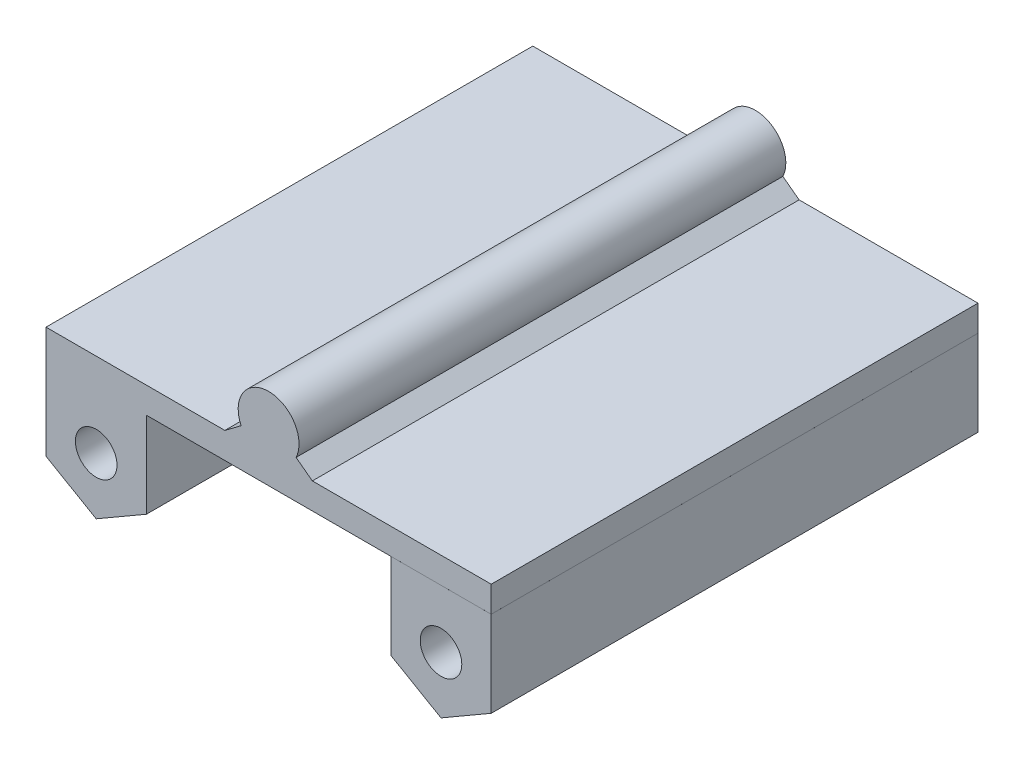
SolidWorks part; units mm, degrees
ref_plane "Front Plane" through (0, 0, 0) normal (0, 0, 1) x (1, 0, 0)
ref_plane "Top Plane" through (0, 0, 0) normal (0, 1, 0) x (1, 0, 0)
ref_plane "Right Plane" through (0, 0, 0) normal (1, 0, 0) x (0, 0, -1)
sketch "Sketch3" plane through (0, 0, 0) normal (0, 0, 1) x (1, 0, 0)
  line L0 (0, 0) -> (4.95, 0)
  line L1 (4.95, 0) -> (4.95, -4.23)
  line L2 (0, 0) -> (0, -4.23)
  line L3 (0, -4.23) -> (2.475, -5.6632)
  line L4 (2.475, -5.6632) -> (4.95, -4.23)
  line L5 (0, 0) -> (10.9749, 0)
  line L6 (14.6231, 0.3758) -> (13.8212, 0.9775)
  line L7 (0, 5) -> (10.975, 5)
  line L18 (17, 0) -> (21.95, 0)
  line L19 (21.95, 0) -> (21.95, -4.23)
  line L20 (17, 0) -> (17, -4.23)
  line L21 (17, -4.23) -> (19.475, -5.6632)
  line L22 (19.475, -5.6632) -> (21.95, -4.23)
  line L23 (13.1316, 1.2844) -> (12.3297, 1.8861)
  line L24 (21.95, 0) -> (21.95, 5)
  line L25 (21.95, 5) -> (10.975, 5)
  line L26 (0, 5) -> (13.7023, 5)
  line L27 (21.9498, -0.0005) -> (10.9749, 0)
  line L28 (0, 0) -> (0, 1.2845)
  line L29 (0, 1.2845) -> (8.8183, 1.2845)
  line L30 (0, 1.2845) -> (0, 0)
  line L31 (21.9498, -0.0005) -> (16.9998, -0.0003)
  line L32 (8.8183, 1.2845) -> (9.6203, 1.8861)
  line L33 (21.9499, 1.284) -> (13.1316, 1.2844)
  line L34 (21.9498, -0.0005) -> (21.9499, 1.284)
  line L35 (10.3099, 0.3759) -> (11.1118, 0.9776)
  arc A1 (12.3297, 1.8861) -> (9.6203, 1.8861) centre (10.975, 2.5301) ccw
  arc A2 (13.8212, 0.9775) -> (11.1118, 0.9776) centre (12.4665, 1.6216) ccw
  dimension "D4" = 3
  dimension "D1" = 4.23
  dimension "D2" = 2.86
  dimension "D3" = 4.23
  dimension "D6" = 5
  dimension "D7" = 2.86
  dimension "D8" = 12.05
  dimension "D9" = 10.975
extrude "Boss-Extrude2" add sketch "Sketch3" along normal blind 24 contours L23 A1 L32 L29 L28 L0 L5 L27 L20 L18 L34 L33 | L3 L4 L1 L0 L2 | L34 L27 L20 L21 L22 L19 L18
sketch "Sketch4" plane through (0, 0, 24) normal (0, 0, 1) x (1, 0, 0)
  line L0 (8.8183, 1.2845) -> (9.6203, 1.8861)
  line L1 (8.8183, 1.2845) -> (9.6203, 1.8861) construction
sketch "Sketch6" plane through (0, 0, 24) normal (0, 0, 1) x (1, 0, 0)
  circle A0 centre (2.475, -2.8632) radius 1.025
  circle A1 centre (19.475, -2.8632) radius 1.025
  dimension "D1" = 2.05
  dimension "D2" = 2.8
  dimension "D3" = 2.05
  dimension "D4" = 2.8
extrude "Cut-Extrude1" cut sketch "Sketch6" against normal blind 5 contours A0 | A1
sketch "Sketch7" plane through (0, 0, 0) normal (0, 0, -1) x (-1, 0, 0)
  line L0 (-2.475, -5.6632) -> (-2.475, -2.8632)
  circle A0 centre (-19.475, -2.8632) radius 1.025
  circle A1 centre (-2.475, -2.8632) radius 1.025
  dimension "D1" = 2.05
  dimension "D2" = 2.8
  dimension "D3" = 2.05
  dimension "D4" = 2.8
extrude "Cut-Extrude2" cut sketch "Sketch7" against normal blind 5
sketch "Sketch8" plane through (0, 0, 5) normal (0, 0, -1) x (-1, 0, 0)
  line L0 (-19.475, -2.8632) -> (-18.45, -2.8632)
  line L1 (-2.475, -2.8632) -> (-1.45, -2.8632)
  line L2 (-18.609, -2.8632) -> (-19.042, -2.1132)
  line L3 (-19.042, -2.1132) -> (-19.908, -2.1132)
  line L4 (-19.908, -2.1132) -> (-20.341, -2.8632)
  line L5 (-20.341, -2.8632) -> (-19.908, -3.6132)
  line L6 (-19.908, -3.6132) -> (-19.042, -3.6132)
  line L7 (-19.042, -3.6132) -> (-18.609, -2.8632)
  line L9 (-1.45, -2.8632) -> (-1.9625, -1.9755)
  line L10 (-1.9625, -1.9755) -> (-2.9875, -1.9755)
  line L11 (-2.9875, -1.9755) -> (-3.5, -2.8632)
  line L12 (-3.5, -2.8632) -> (-2.9875, -3.7508)
  line L13 (-2.9875, -3.7508) -> (-1.9625, -3.7508)
  line L14 (-1.9625, -3.7508) -> (-1.45, -2.8632)
  circle A0 centre (-19.475, -2.8632) radius 1.025 construction
  circle A1 centre (-19.475, -2.8632) radius 0.75 construction
  circle A2 centre (-2.475, -2.8632) radius 1.025 construction
  circle A3 centre (-2.475, -2.8632) radius 0.8877 construction
extrude "Cut-Extrude4" cut sketch "Sketch8" against normal blind 7000
